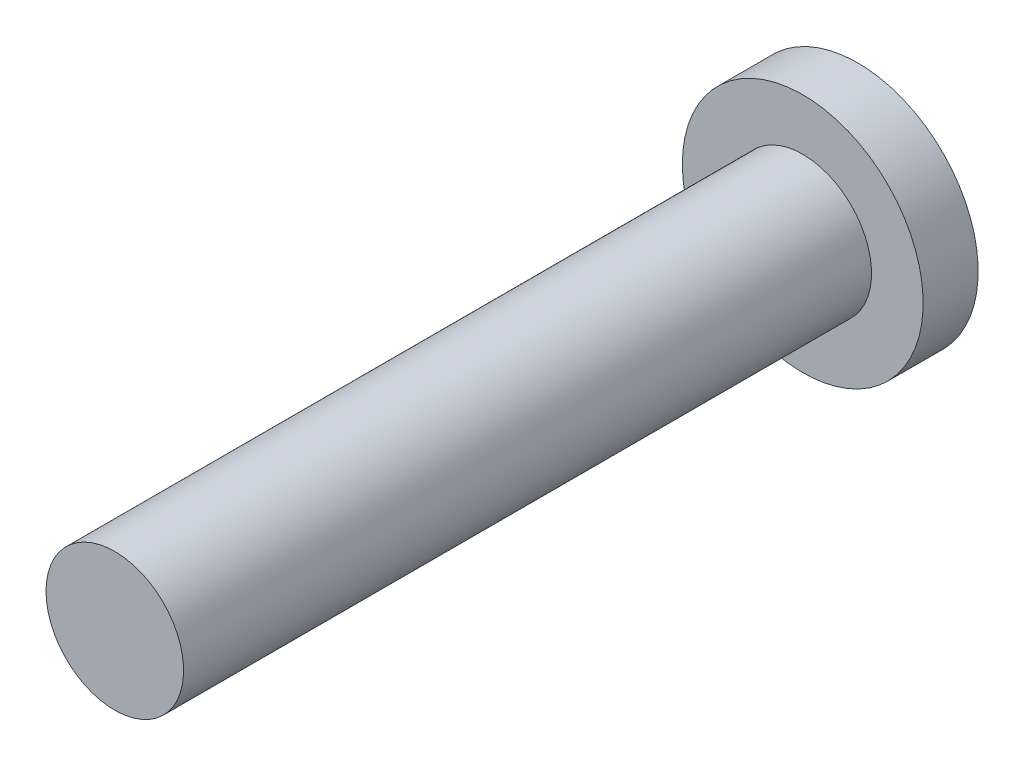
SolidWorks part; units mm, degrees
ref_plane "Front Plane" through (0, 0, 0) normal (0, 0, 1) x (1, 0, 0)
ref_plane "Top Plane" through (0, 0, 0) normal (0, 1, 0) x (1, 0, 0)
ref_plane "Right Plane" through (0, 0, 0) normal (1, 0, 0) x (0, 0, -1)
sketch "Sketch1" plane through (0, 0, 0) normal (0, 1, 0) x (1, 0, 0)
  line L0 (0, -117.2331) -> (0, 5744.4225) construction
  line L1 (0, 0) -> (1, 0)
  line L2 (1, 0) -> (1, 10)
  line L3 (1, 10) -> (1.75, 10)
  line L4 (1.75, 10) -> (1.75, 10.8)
  line L5 (1.75, 10.8) -> (0, 10.8)
  line L6 (0, 10.8) -> (0, 0)
  dimension "D1" = 1.75
  dimension "D2" = 1
  dimension "D3" = 10
  dimension "D4" = 0.75
  dimension "D5" = 0.8
revolve "Revolve1" add sketch "Sketch1" angle 360 about L6
